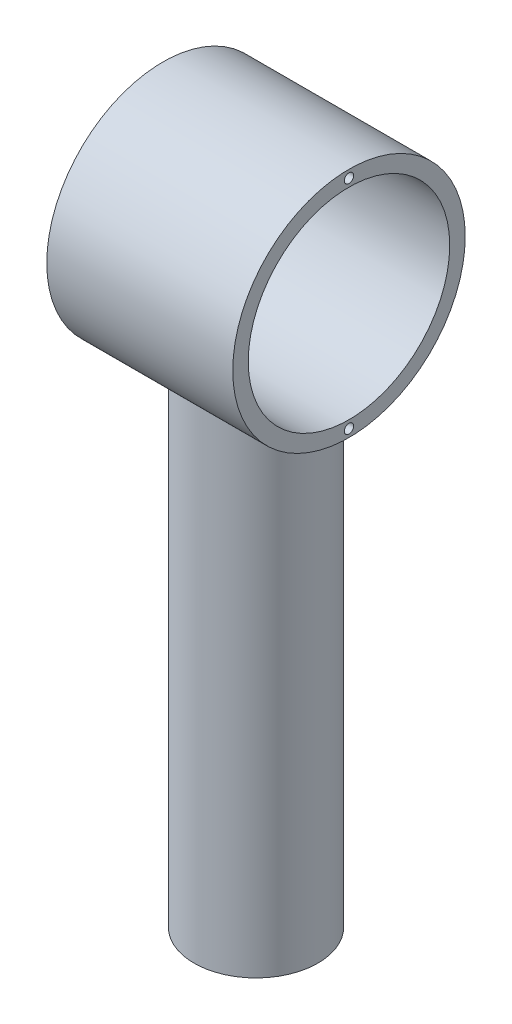
SolidWorks part; units mm, degrees
ref_plane "Front Plane" through (0, 0, 0) normal (0, 0, 1) x (1, 0, 0)
ref_plane "Top Plane" through (0, 0, 0) normal (0, 1, 0) x (1, 0, 0)
ref_plane "Right Plane" through (0, 0, 0) normal (1, 0, 0) x (0, 0, -1)
sketch "Sketch1" plane through (0, 0, 0) normal (0, 1, 0) x (1, 0, 0)
  line L3 (14.4338, 0) -> (7.2169, 12.5)
  line L4 (7.2169, 12.5) -> (-7.2169, 12.5)
  line L5 (-7.2169, 12.5) -> (-14.4338, 0)
  line L6 (-14.4338, 0) -> (-7.2169, -12.5)
  line L7 (-7.2169, -12.5) -> (7.2169, -12.5)
  line L8 (7.2169, -12.5) -> (14.4338, 0)
  circle A0 centre (0, 0) radius 20
  circle A1 centre (0, 0) radius 12.5 construction
  dimension "D1" = 40
extrude "Boss-Extrude1" add sketch "Sketch1" along normal blind 25
sketch "Sketch2" plane through (0, 0, 0) normal (0, -1, 0) x (1, 0, 0)
  circle A1 centre (0, 0) radius 20
extrude "Boss-Extrude2" add sketch "Sketch2" along normal blind 100
ref_plane "Plane1" through (20, 0, 0) normal (1, 0, 0) x (0, 0, -1)
sketch "Sketch5" plane through (0, 0, 0) normal (0, 1, 0) x (1, 0, 0)
  line L1 (14.4338, 0) -> (7.2169, 12.5)
  line L2 (7.2169, 12.5) -> (-7.2169, 12.5)
  line L3 (-7.2169, 12.5) -> (-14.4338, 0)
  line L4 (-14.4338, 0) -> (-7.2169, -12.5)
  line L5 (-7.2169, -12.5) -> (7.2169, -12.5)
  line L6 (7.2169, -12.5) -> (14.4338, 0)
  circle A0 centre (0, 0) radius 12.5 construction
sketch "Sketch6" plane through (0, 25, 0) normal (0, 1, 0) x (1, 0, 0)
  circle A0 centre (0, 0) radius 20
  dimension "D1" = 40
extrude "Boss-Extrude4" add sketch "Sketch6" against normal blind 100
sketch "Sketch7" plane through (20, 0, 0) normal (1, 0, 0) x (0, 0, -1)
  circle A2 centre (0, 39.2866) radius 25
  dimension "D3" = 50
extrude "Cut-Extrude2" cut sketch "Sketch7" against normal blind 40
sketch "Sketch8" plane through (20, 0, 0) normal (1, 0, 0) x (0, 0, -1)
  circle A0 centre (0, 39.2528) radius 25
  circle A1 centre (0, 39.2528) radius 22.5
  dimension "D1" = 50
  dimension "D2" = 45
extrude "Boss-Extrude7" add sketch "Sketch8" against normal blind 40 contours A1 | A0
sketch "Sketch9" plane through (20, 0, 0) normal (1, 0, 0) x (0, 0, -1)
  circle A0 centre (0, 39.2528) radius 25
extrude "Boss-Extrude8" add sketch "Sketch9" against normal blind 2
sketch "Sketch10" plane through (18, 0, 0) normal (-1, 0, 0) x (0, 0, 1)
  line L1 (-15.0811, 22.5552) -> (15.0811, 22.5552)
  arc A1 (-15.0811, 22.5552) -> (15.0811, 22.5552) centre (0, 39.2528) ccw
extrude "Boss-Extrude10" add sketch "Sketch10" along normal blind 38
sketch "Sketch11" plane through (0, -100, 0) normal (0, -1, 0) x (1, 0, 0)
  line L0 (0, 20) -> (0, 0)
  line L1 (0, 0) -> (20, 0)
  line L2 (20, -27.5) -> (20, 27.5) construction
  line L4 (0, 14.4338) -> (-12.5, 7.2169)
  line L5 (-12.5, 7.2169) -> (-12.5, -7.2169)
  line L6 (-12.5, -7.2169) -> (0, -14.4338)
  line L7 (0, -14.4338) -> (12.5, -7.2169)
  line L8 (12.5, -7.2169) -> (12.5, 7.2169)
  line L9 (12.5, 7.2169) -> (0, 14.4338)
  arc A0 (20, 0) -> (-20, 0) centre (0, 0) ccw construction
  circle A1 centre (0, 0) radius 12.5 construction
extrude "Cut-Extrude3" cut sketch "Sketch11" against normal blind 25 contours L8 L9 L0 L1 | L7 L8 L1 L0 L4 L5 L6
sketch "Sketch12" plane through (20, 0, 0) normal (1, 0, 0) x (0, 0, -1)
  circle A0 centre (0, 39.2528) radius 25
extrude "Cut-Extrude4" cut sketch "Sketch12" against normal blind 75
sketch "Sketch13" plane through (20, 0, 0) normal (1, 0, 0) x (0, 0, -1)
  circle A0 centre (0, 39.3347) radius 37.5
  dimension "D1" = 75
sketch "Sketch14" plane through (0, -100, 0) normal (0, -1, 0) x (1, 0, 0)
  line L1 (0, -14.4338) -> (12.5, -7.2169)
  line L2 (12.5, -7.2169) -> (12.5, 7.2169)
  line L3 (12.5, 7.2169) -> (0, 14.4338)
  line L4 (0, 14.4338) -> (-12.5, 7.2169)
  line L5 (-12.5, 7.2169) -> (-12.5, -7.2169)
  line L6 (-12.5, -7.2169) -> (0, -14.4338)
  circle A0 centre (0, 0) radius 12.5 construction
  circle A1 centre (0, 0) radius 20
extrude "Boss-Extrude11" add sketch "Sketch14" along normal blind 50
extrude "Boss-Extrude12" add sketch "Sketch13" against normal blind 50 and the other way blind 10
sketch "Sketch16" plane through (30, 0, 0) normal (1, 0, 0) x (0, 0, -1)
  line L0 (-17.3205, 17.3347) -> (17.3205, 17.3347)
  line L1 (0, 67.3347) -> (24.1903, 67.3347)
  circle A0 centre (0, 39.3347) radius 28
  dimension "D1" = 56
  dimension "D2" = 50
sketch "Sketch17" plane through (30, 0, 0) normal (1, 0, 0) x (0, 0, -1)
  circle A0 centre (0, 39.3347) radius 32.5
  dimension "D1" = 65
extrude "Cut-Extrude5" cut sketch "Sketch17" against normal blind 50 contours A0
sketch "Sketch18" plane through (30, 0, 0) normal (1, 0, 0) x (0, 0, -1)
  circle A0 centre (0, 39.3347) radius 32.5
  circle A1 centre (0, 39.3347) radius 37.5
extrude "Boss-Extrude13" add sketch "Sketch18" along normal blind 2
sketch "Sketch19" plane through (32, 0, 0) normal (1, 0, 0) x (0, 0, -1)
  line L0 (0, 71.8347) -> (0, 76.8347)
  line L1 (0, 76.8347) -> (0, 74.3347)
  line L2 (0, 74.3347) -> (3.9271, 74.3347)
  line L3 (0, 6.8347) -> (0, 1.8347)
  line L4 (0, 1.8347) -> (0, 4.3347)
  line L5 (0, 4.3347) -> (3.9271, 4.3347)
  circle A0 centre (0, 39.3347) radius 32.5 construction
  circle A1 centre (0, 39.3347) radius 32.5 construction
  circle A2 centre (0, 39.3347) radius 37.5 construction
  arc A3 (-20, 7.6133) -> (20, 7.6133) centre (0, 39.3347) ccw construction
sketch "Sketch21" plane through (32, 0, 0) normal (1, 0, 0) x (0, 0, -1)
  circle A0 centre (0, 39.3347) radius 32.5
  circle A1 centre (0, 39.3347) radius 37.5
extrude "Cut-Extrude6" cut sketch "Sketch21" against normal blind 2
sketch "Sketch22" plane through (30, 0, 0) normal (1, 0, 0) x (0, 0, -1)
  circle A0 centre (0, 74.3347) radius 1.5
  circle A1 centre (0, 4.3347) radius 1.5
  dimension "D1" = 3
  dimension "D2" = 3
extrude "Cut-Extrude7" cut sketch "Sketch22" against normal blind 10
